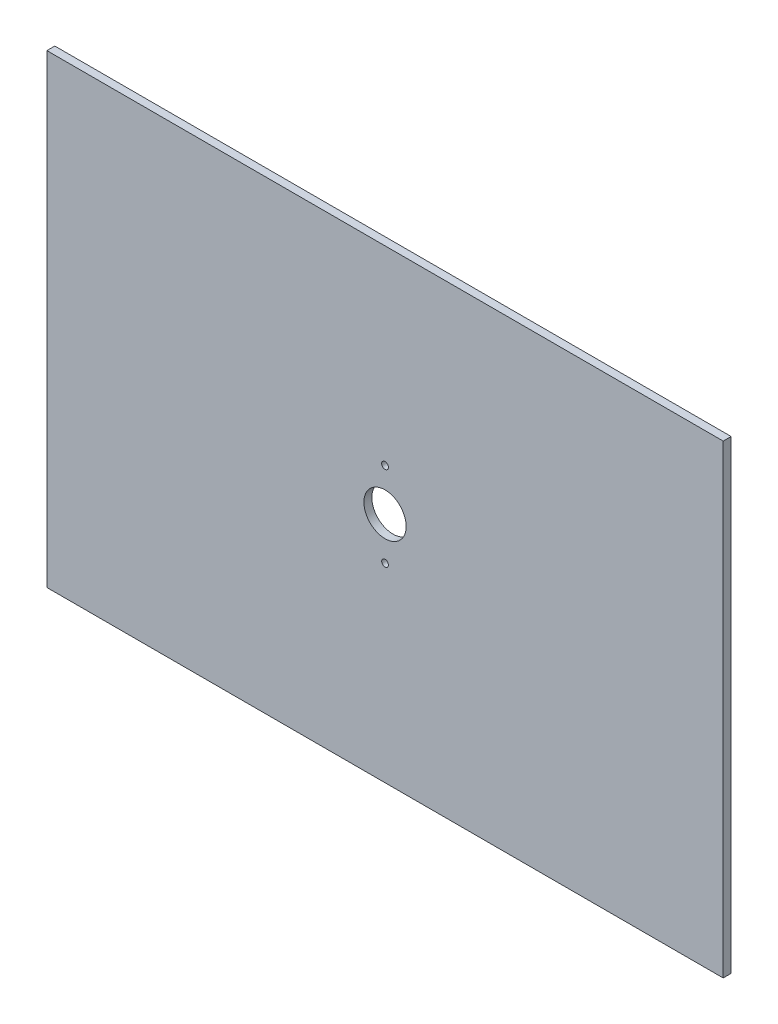
SolidWorks part; units mm, degrees
ref_plane "Front Plane" through (0, 0, 0) normal (0, 0, 1) x (1, 0, 0)
ref_plane "Top Plane" through (0, 0, 0) normal (0, 1, 0) x (1, 0, 0)
ref_plane "Right Plane" through (0, 0, 0) normal (1, 0, 0) x (0, 0, -1)
sketch "Sketch1" plane through (0, 0, 0) normal (0, 0, 1) x (1, 0, 0)
  line L1 (0, 0) -> (-406.4, 0)
  line L2 (0, 0) -> (0, 279.4)
  line L3 (0, 279.4) -> (-406.4, 279.4)
  line L4 (-406.4, 0) -> (-406.4, 279.4)
  dimension "D1" = 279.4
  dimension "D2" = 406.4
extrude "Boss-Extrude1" add sketch "Sketch1" along normal blind 4.7625
sketch "Sketch2" plane through (0, 0, 4.7625) normal (0, 0, 1) x (1, 0, 0)
  line L0 (-203.2, 0) -> (-203.2, 279.4) construction
  line L1 (-406.4, 0) -> (0, 0) construction
  line L2 (0, 279.4) -> (-406.4, 279.4) construction
  line L3 (-406.4, 279.4) -> (-406.4, 0) construction
  line L4 (-406.4, 139.7) -> (0, 139.7) construction
  line L5 (0, 0) -> (0, 279.4) construction
  circle A0 centre (-203.2, 139.7) radius 12.7
  dimension "D2" = 25.4
  dimension "D1" = 203.2
extrude "Cut-Extrude1" cut sketch "Sketch2" against normal up to surface (4.7625 mm away) up to face at (-203.2, 139.7, 0)
sketch "Sketch3" plane through (0, 0, 0) normal (0, 0, -1) x (-1, 0, 0)
  circle A1 centre (203.2, 114.3) radius 2.032
  circle A2 centre (203.2, 165.1) radius 2.032
  circle A3 centre (203.2, 139.7) radius 12.7 construction
  dimension "D1" = 25.4
  dimension "D2" = 25.4
extrude "Cut-Extrude2" cut sketch "Sketch3" against normal up to surface (4.7625 mm away) up to face at (-190.5, 139.7, 4.7625)
